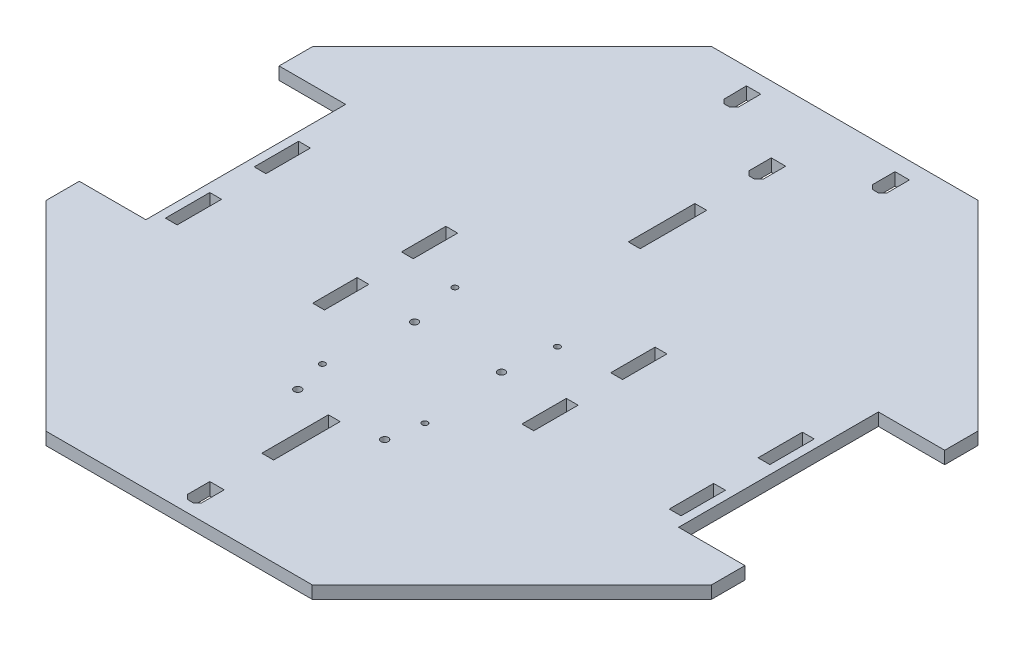
SolidWorks part; units mm, degrees
ref_plane "Front Plane" through (0, 0, 0) normal (0, 0, 1) x (1, 0, 0)
ref_plane "Top Plane" through (0, 0, 0) normal (0, 1, 0) x (1, 0, 0)
ref_plane "Right Plane" through (0, 0, 0) normal (1, 0, 0) x (0, 0, -1)
sketch "Sketch1" plane through (0, 0, 0) normal (0, 1, 0) x (1, 0, 0)
  line L1 (0, 0) -> (254, 0)
  line L2 (0, 0) -> (0, 254)
  line L3 (0, 254) -> (254, 254)
  line L4 (254, 0) -> (254, 254)
  dimension "D1" = 254
  dimension "D2" = 254
extrude "Boss-Extrude1" add sketch "Sketch1" along normal blind 4.8
sketch "Sketch2" plane through (0, 4.8, 0) normal (0, 1, 0) x (1, 0, 0)
  line L0 (0, 254) -> (76.2, 254) construction
  line L1 (254, 254) -> (0, 254) construction
  line L2 (0, 254) -> (0, 177.8) construction
  line L3 (0, 254) -> (0, 0) construction
sketch "Sketch4" plane through (0, 4.8, 0) normal (0, 1, 0) x (1, 0, 0)
  line L0 (76.2, 254) -> (0, 177.8)
  line L1 (0, 177.8) -> (0, 254)
  line L2 (0, 254) -> (76.2, 254)
extrude "Cut-Extrude2" cut sketch "Sketch4" against normal through all
sketch "Sketch5" plane through (0, 4.8, 0) normal (0, 1, 0) x (1, 0, 0)
  line L0 (177.8, 254) -> (254, 254) construction
  line L1 (254, 254) -> (76.2, 254) construction
  line L2 (254, 254) -> (254, 177.8) construction
  line L3 (254, 0) -> (254, 254) construction
  line L4 (177.8, 254) -> (254, 177.8)
  line L5 (254, 177.8) -> (254, 254)
  line L6 (254, 254) -> (177.8, 254)
extrude "Cut-Extrude3" cut sketch "Sketch5" against normal blind 4.826
sketch "Sketch9" plane through (0, 4.8, 0) normal (0, 1, 0) x (1, 0, 0)
  line L0 (0, 76.2) -> (0, 0)
  line L1 (0, 177.8) -> (0, 0) construction
  line L2 (0, 0) -> (76.2, 0)
  line L3 (0, 0) -> (254, 0) construction
  line L4 (76.2, 0) -> (0, 76.2)
  dimension "D1" = 76.2
  dimension "D2" = 76.2
extrude "Cut-Extrude5" cut sketch "Sketch9" against normal blind 4.826
sketch "Sketch11" plane through (0, 4.8, 0) normal (0, 1, 0) x (1, 0, 0)
  line L0 (254, 76.2) -> (254, 0)
  line L1 (254, 0) -> (254, 177.8) construction
  line L2 (254, 0) -> (177.8, 0)
  line L3 (76.2, 0) -> (254, 0) construction
  line L4 (177.8, 0) -> (254, 76.2)
  dimension "D1" = 76.2
  dimension "D2" = 76.2
extrude "Cut-Extrude6" cut sketch "Sketch11" against normal blind 4.826
sketch "Sketch16" plane through (0, 0, 0) normal (0, -1, 0) x (1, 0, 0)
  line L3 (155.3, -247.65) -> (155.3, -237.45) construction
  line L8 (254, -76.2) -> (177.8, 0)
  line L9 (177.8, 0) -> (76.2, 0)
  line L10 (76.2, 0) -> (0, -76.2)
  line L11 (0, -76.2) -> (0, -177.8)
  line L12 (0, -177.8) -> (76.2, -254)
  line L13 (76.2, -254) -> (177.8, -254)
  line L14 (177.8, -254) -> (254, -177.8)
  line L15 (254, -177.8) -> (254, -76.2)
  line L16 (254, -76.2) -> (177.8, 0)
  line L17 (177.8, 0) -> (76.2, 0)
  line L18 (76.2, 0) -> (0, -76.2)
  line L19 (0, -76.2) -> (0, -177.8)
  line L20 (0, -177.8) -> (76.2, -254)
  line L21 (76.2, -254) -> (177.8, -254)
  line L22 (177.8, -254) -> (254, -177.8)
  line L23 (254, -177.8) -> (254, -76.2)
  line L43 (154.05, -237.45) -> (152.4, -239.0996)
  line L45 (154.05, -237.45) -> (156.25, -237.45)
  line L46 (157.9, -239.0996) -> (156.25, -237.45)
  line L47 (157.9, -239.0996) -> (157.9, -240.05)
  line L48 (157.9, -240.05) -> (157.9, -241.75)
  line L49 (157.9, -241.75) -> (157.9, -242.075)
  line L50 (157.9, -243.025) -> (157.9, -243.35)
  line L51 (157.9, -242.075) -> (157.9, -243.025)
  line L52 (157.9, -243.35) -> (157.9, -246.2837)
  line L53 (157.9, -246.2837) -> (157.9, -247.2337)
  line L54 (157.9, -247.2337) -> (157.9, -247.65)
  line L55 (157.9, -247.65) -> (152.4, -247.65)
  line L57 (152.4, -247.65) -> (152.4, -239.0996)
  point P24 (155.3, -237.45)
  point P28 (155.3, -247.65)
  dimension "D4" = 2.2
  dimension "D3" = 101.6
  dimension "D5" = 6.35
extrude "Cut-Extrude8" cut sketch "Sketch16" against normal through all flip side to cut
sketch "Sketch17" plane through (0, 0, 0) normal (0, -1, 0) x (1, 0, 0)
  line L8 (254, -76.2) -> (177.8, 0)
  line L9 (177.8, 0) -> (76.2, 0)
  line L10 (76.2, 0) -> (0, -76.2)
  line L11 (0, -76.2) -> (0, -177.8)
  line L12 (0, -177.8) -> (76.2, -254)
  line L13 (76.2, -254) -> (177.8, -254)
  line L14 (177.8, -254) -> (254, -177.8)
  line L15 (254, -177.8) -> (254, -76.2)
  line L16 (254, -76.2) -> (177.8, 0)
  line L17 (177.8, 0) -> (76.2, 0)
  line L18 (76.2, 0) -> (0, -76.2)
  line L19 (0, -76.2) -> (0, -177.8)
  line L20 (0, -177.8) -> (76.2, -254)
  line L21 (76.2, -254) -> (177.8, -254)
  line L22 (177.8, -254) -> (254, -177.8)
  line L23 (254, -177.8) -> (254, -76.2)
  line L38 (125.9, -218.4) -> (128.1, -218.4)
  line L39 (129.75, -220.0496) -> (128.1, -218.4)
  line L40 (129.75, -220.0496) -> (129.75, -221)
  line L41 (129.75, -221) -> (129.75, -222.7)
  line L42 (129.75, -222.7) -> (129.75, -223.025)
  line L43 (129.75, -223.025) -> (129.75, -223.975)
  line L44 (129.75, -223.975) -> (129.75, -224.3)
  line L45 (125.9, -218.4) -> (124.25, -220.0496)
  line L46 (124.25, -221) -> (124.25, -220.0496)
  line L47 (124.25, -222.7) -> (124.25, -221)
  line L48 (124.25, -223.025) -> (124.25, -222.7)
  line L49 (124.25, -223.025) -> (124.25, -223.975)
  line L50 (124.25, -224.3) -> (124.25, -223.975)
  line L51 (124.25, -228.6) -> (124.25, -228.1837)
  line L52 (124.25, -228.15) -> (124.25, -227.2337)
  line L53 (124.25, -227.2337) -> (124.25, -224.3)
  line L54 (129.75, -224.3) -> (129.75, -227.2337)
  line L55 (129.75, -227.2337) -> (129.75, -228.1837)
  line L56 (129.75, -228.1837) -> (129.75, -228.6)
  line L57 (129.75, -228.6) -> (124.25, -228.6)
  line L58 (124.25, -228.1837) -> (124.25, -228.15)
  line L59 (127, -228.6) -> (127, -218.4) construction
  dimension "D3" = 127
  dimension "D4" = 2.2
extrude "Cut-Extrude17" cut sketch "Sketch17" against normal through all flip side to cut
extrude "Cut-Extrude18" cut sketch "Sketch18" against normal through all flip side to cut
sketch "Sketch18" plane through (166.6617, 4.8, -135.9887) normal (0, 1, 0) x (1, 0, 0)
  line L1 (-65.4617, 103.1109) -> (-65.4617, 111.6613)
  line L16 (-90.5617, -135.9887) -> (11.0383, -135.9887)
  line L17 (11.0383, -135.9887) -> (87.2383, -59.7887)
  line L18 (87.2383, -59.7887) -> (87.2383, 41.8113)
  line L19 (87.2383, 41.8113) -> (11.0383, 118.0113)
  line L20 (11.0383, 118.0113) -> (-90.5617, 118.0113)
  line L21 (-90.5617, 118.0113) -> (-166.7617, 41.8113)
  line L22 (-166.7617, 41.8113) -> (-166.7617, -59.7887)
  line L23 (-166.7617, -59.7887) -> (-90.5617, -135.9887)
  line L43 (-69.2117, 101.4613) -> (-70.8124, 103.0617)
  line L44 (-69.2117, 101.4613) -> (-67.0117, 101.4613)
  line L45 (-65.4617, 103.1109) -> (-67.0117, 101.4613)
  line L51 (-65.4617, 111.6613) -> (-70.9617, 111.6613)
  line L54 (-70.8124, 103.0617) -> (-70.9617, 111.6613)
  dimension "D3" = 6.35
extrude "Cut-Extrude19" cut sketch "Sketch19" against normal through all flip side to cut
sketch "Sketch19" plane through (277.6323, 0, -234.2881) normal (0, -1, 0) x (1, 0, 0)
  line L0 (-23.6323, 158.0881) -> (-23.6323, 56.4881) construction
  line L2 (-99.9323, -19.7119) -> (-201.4323, -19.7119) construction
  line L16 (-23.6323, 158.0881) -> (-99.8323, 234.2881)
  line L17 (-99.8323, 234.2881) -> (-201.4323, 234.2881)
  line L18 (-201.4323, 234.2881) -> (-277.6323, 158.0881)
  line L19 (-277.6323, 158.0881) -> (-277.6323, 56.4881)
  line L20 (-277.6323, 56.4881) -> (-201.4323, -19.7119)
  line L21 (-201.4323, -19.7119) -> (-99.8323, -19.7119)
  line L22 (-99.8323, -19.7119) -> (-23.6323, 56.4881)
  line L23 (-23.6323, 56.4881) -> (-23.6323, 158.0881)
  line L33 (-56.8343, 124.2214) -> (-52.3343, 124.2214)
  line L34 (-56.8343, 124.2214) -> (-56.8343, 141.1547)
  line L35 (-56.8343, 141.1547) -> (-52.3343, 141.1547)
  line L36 (-52.3343, 124.2214) -> (-52.3343, 141.1547)
  line L37 (-56.8343, 124.2214) -> (-52.3343, 141.1547) construction
  line L38 (-56.8343, 141.1547) -> (-52.3343, 124.2214) construction
  line L41 (-56.8343, 90.3547) -> (-52.3343, 90.3547)
  line L42 (-56.8343, 90.3547) -> (-56.8343, 107.2881)
  line L43 (-56.8343, 107.2881) -> (-52.3343, 107.2881)
  line L44 (-52.3343, 90.3547) -> (-52.3343, 107.2881)
  line L45 (-56.8343, 90.3547) -> (-52.3343, 107.2881) construction
  line L46 (-56.8343, 107.2881) -> (-52.3343, 90.3547) construction
  dimension "D1" = 28.702
  dimension "D2" = 28.702
  dimension "D4" = 16.9333
  dimension "D3" = 143.9333
  dimension "D5" = 4.5
  dimension "D6" = 16.9333
  dimension "D7" = 4.5
  dimension "D8" = 16.9333
ref_plane "Plane2" through (126.95, 0, 0) normal (1, 0, 0) x (0, 0, -1)
mirror "Mirror2" about plane through (126.95, 0, 0) normal (1, 0, 0) of "Cut-Extrude19"
extrude "Cut-Extrude22" cut sketch "Sketch32" against normal blind 25.4
sketch "Sketch32" plane through (254, 6.7388, -234.2881) normal (1, 0, 0) x (0, 1, 0)
  line L1 (-6.7388, 145.3881) -> (-1.9388, 145.3881)
  line L2 (-6.7388, 145.3881) -> (-6.7388, 69.1881)
  line L3 (-6.7388, 69.1881) -> (-1.9388, 69.1881)
  line L4 (-1.9388, 145.3881) -> (-1.9388, 69.1881)
  line L5 (-6.7388, 145.3881) -> (-1.9388, 69.1881) construction
  line L6 (-6.7388, 69.1881) -> (-1.9388, 145.3881) construction
  point P4 (-4.3388, 107.2881)
extrude "Cut-Extrude23" cut sketch "Sketch33" against normal through all contours L53 L44 L45 L46 L47 L48 L49 L50 L51 L38 L39 L52 L41 L42 L43
sketch "Sketch33" plane through (166.6617, 0, -135.9887) normal (0, -1, 0) x (1, 0, 0)
  line L0 (-39.8327, 121.3869) -> (-39.8327, 131.5869)
  line L24 (62.1673, 47.0887) -> (87.1673, 47.0887)
  line L25 (87.1673, 47.0887) -> (87.1673, 59.7887)
  line L26 (87.1673, 59.7887) -> (10.9673, 135.9887)
  line L27 (10.9673, 135.9887) -> (-90.6327, 135.9887)
  line L28 (-90.6327, 135.9887) -> (-166.8327, 59.7887)
  line L29 (-166.8327, 59.7887) -> (-166.8327, 47.0887)
  line L30 (-166.8327, -41.8113) -> (-90.6327, -118.0113)
  line L31 (-90.6327, -118.0113) -> (10.9673, -118.0113)
  line L32 (10.9673, -118.0113) -> (87.1673, -41.8113)
  line L33 (87.1673, -41.8113) -> (87.1673, -29.1113)
  line L34 (87.1673, -29.1113) -> (62.1673, -29.1113)
  line L35 (62.1673, -29.1113) -> (62.1673, 47.0887)
  line L38 (-42.5827, 122.7532) -> (-42.5827, 125.6869)
  line L39 (-42.5827, 121.8369) -> (-42.5827, 122.7532)
  line L41 (-37.0827, 121.3869) -> (-42.5827, 121.3869)
  line L42 (-37.0827, 121.8032) -> (-37.0827, 121.3869)
  line L43 (-37.0827, 122.7532) -> (-37.0827, 121.8032)
  line L44 (-37.0827, 129.9373) -> (-38.7327, 131.5869)
  line L45 (-40.9327, 131.5869) -> (-38.7327, 131.5869)
  line L46 (-40.9327, 131.5869) -> (-42.5827, 129.9373)
  line L47 (-42.5827, 128.9869) -> (-42.5827, 129.9373)
  line L48 (-42.5827, 127.2869) -> (-42.5827, 128.9869)
  line L49 (-42.5827, 126.9619) -> (-42.5827, 127.2869)
  line L50 (-42.5827, 126.9619) -> (-42.5827, 126.0119)
  line L51 (-42.5827, 125.6869) -> (-42.5827, 126.0119)
  line L52 (-42.5827, 121.8369) -> (-42.5827, 121.3869)
  line L53 (-37.0827, 122.7532) -> (-37.0827, 129.9373)
  line L71 (-141.8327, -29.1113) -> (-166.8327, -29.1113)
  line L73 (-166.8327, -29.1113) -> (-166.8327, -41.8113)
  line L75 (-166.8327, 47.0887) -> (-141.8327, 47.0887)
  line L77 (-141.8327, 47.0887) -> (-141.8327, -29.1113)
  point P7 (-39.8327, 131.5869)
  point P15 (-39.8327, 121.3869)
  dimension "D3" = 127
extrude "Cut-Extrude24" cut sketch "Sketch34" against normal blind 25.4
sketch "Sketch34" plane through (0, 6.7388, -234.2881) normal (-1, 0, 0) x (0, -1, 0)
  line L3 (6.7388, 69.1881) -> (1.9388, 69.1881)
  line L8 (6.7388, 69.1881) -> (6.7388, 145.3881)
  line L9 (6.7388, 145.3881) -> (1.9388, 145.3881)
  line L10 (1.9388, 69.1881) -> (1.9388, 145.3881)
  line L11 (6.7388, 69.1881) -> (1.9388, 145.3881) construction
  line L12 (6.7388, 145.3881) -> (1.9388, 69.1881) construction
  point P17 (4.3388, 107.2881)
extrude "Cut-Extrude26" cut sketch "Sketch36" against normal through all
sketch "Sketch36" plane through (277.6323, 0, -234.2881) normal (0, -1, 0) x (1, 0, 0)
  line L0 (-49.0323, 69.1881) -> (-49.0323, 145.3881) construction
  line L1 (-108.5209, 124.2214) -> (-113.0209, 124.2214)
  line L2 (-108.5209, 124.2214) -> (-108.5209, 141.1547)
  line L3 (-108.5209, 141.1547) -> (-113.0209, 141.1547)
  line L4 (-113.0209, 124.2214) -> (-113.0209, 141.1547)
  line L5 (-108.5209, 124.2214) -> (-113.0209, 141.1547) construction
  line L6 (-108.5209, 141.1547) -> (-113.0209, 124.2214) construction
  line L10 (-113.0209, 90.3547) -> (-108.5209, 90.3547)
  line L11 (-113.0209, 90.3547) -> (-113.0209, 107.2881)
  line L12 (-113.0209, 107.2881) -> (-108.5209, 107.2881)
  line L13 (-108.5209, 90.3547) -> (-108.5209, 107.2881)
  line L14 (-113.0209, 90.3547) -> (-108.5209, 107.2881) construction
  line L15 (-113.0209, 107.2881) -> (-108.5209, 90.3547) construction
  point P4 (-110.3603, 132.9109)
  point P5 (-110.7709, 141.1547)
  point P13 (-110.6536, 98.8214)
  dimension "D7" = 4.5
  dimension "D1" = 16.9333
  dimension "D2" = 16.9333
  dimension "D3" = 4.5
  dimension "D4" = 4.5
  dimension "D5" = 59.4886
  dimension "D6" = 59.4886
mirror "Mirror3" about plane through (126.95, 0, 0) normal (1, 0, 0) of "Cut-Extrude26"
sketch "Sketch37" plane through (0, 4.8, 0) normal (0, 1, 0) x (1, 0, 0)
  line L1 (129.25, 173.5667) -> (124.75, 173.5667)
  line L2 (129.25, 173.5667) -> (129.25, 198.9667)
  line L3 (129.25, 198.9667) -> (124.75, 198.9667)
  line L4 (124.75, 173.5667) -> (124.75, 198.9667)
  line L5 (129.25, 173.5667) -> (124.75, 198.9667) construction
  line L6 (129.25, 198.9667) -> (124.75, 173.5667) construction
  line L7 (177.7, 254) -> (76.2, 254) construction
  line L8 (0, 177.8) -> (0, 165.1) construction
  point P4 (127, 186.2667)
  point P5 (127, 198.9667)
  dimension "D1" = 25.4
  dimension "D2" = 4.5
  dimension "D4" = 55.0333
  dimension "D3" = 127
extrude "Cut-Extrude27" cut sketch "Sketch37" against normal through all
sketch "Sketch46" plane through (0, 0, 0) normal (0, -1, 0) x (1, 0, 0)
  line L16 (25.4, -165.1) -> (0, -165.1)
  line L17 (0, -165.1) -> (0, -177.8)
  line L18 (0, -177.8) -> (76.2, -254)
  line L19 (76.2, -254) -> (177.7, -254)
  line L20 (177.7, -254) -> (253.9, -177.8)
  line L21 (177.7, -254) -> (253.9, -177.8)
  line L22 (253.9, -165.1) -> (228.6, -165.1)
  line L23 (228.6, -165.1) -> (228.6, -88.9)
  line L24 (228.6, -88.9) -> (253.9, -88.9)
  line L25 (253.9, -177.8) -> (253.9, -165.1)
  line L26 (253.9, -177.8) -> (253.9, -165.1)
  line L27 (177.7, 0) -> (76.2, 0)
  line L28 (76.2, 0) -> (0, -76.2)
  line L29 (0, -76.2) -> (0, -88.9)
  line L30 (0, -88.9) -> (25.4, -88.9)
  line L31 (25.4, -88.9) -> (25.4, -165.1)
  line L32 (25.4, -165.1) -> (0, -165.1)
  line L33 (0, -165.1) -> (0, -177.8)
  line L34 (0, -177.8) -> (76.2, -254)
  line L35 (76.2, -254) -> (177.7, -254)
  line L38 (253.9, -165.1) -> (228.6, -165.1)
  line L39 (228.6, -165.1) -> (228.6, -88.9)
  line L40 (228.6, -88.9) -> (253.9, -88.9)
  line L43 (177.7, 0) -> (76.2, 0)
  line L44 (76.2, 0) -> (0, -76.2)
  line L45 (0, -76.2) -> (0, -88.9)
  line L46 (0, -88.9) -> (25.4, -88.9)
  line L47 (25.4, -88.9) -> (25.4, -165.1)
  line L48 (253.9, -88.9) -> (253.9, -76.2)
  line L49 (253.9, -88.9) -> (253.9, -76.2)
  line L50 (253.9, -76.2) -> (177.7, 0)
  line L51 (253.9, -76.2) -> (177.7, 0)
  dimension "D1" = 0
sketch "Sketch48" plane through (0, 0, 0) normal (0, -1, 0) x (-1, 0, 0)
  line L0 (-177.7, 0) -> (-76.2, 0) construction
  line L1 (-124.65, 33.8667) -> (-129.15, 33.8667)
  line L2 (-124.65, 33.8667) -> (-124.65, 59.2667)
  line L3 (-124.65, 59.2667) -> (-129.15, 59.2667)
  line L4 (-129.15, 33.8667) -> (-129.15, 59.2667)
  line L5 (-124.65, 33.8667) -> (-129.15, 59.2667) construction
  line L6 (-124.65, 59.2667) -> (-129.15, 33.8667) construction
  line L7 (-253.9, 88.9) -> (-253.9, 76.2) construction
  point P4 (-126.9, 46.5667)
  point P9 (-126.9, 33.8667)
  dimension "D3" = 4.5
  dimension "D1" = 33.8667
  dimension "D2" = 25.4
  dimension "D4" = 127
extrude "Cut-Extrude34" cut sketch "Sketch48" against normal through all
sketch "Sketch49" plane through (0, 0, 0) normal (0, -1, 0) x (1, 0, 0)
  line L16 (25.4, -165.1) -> (0, -165.1)
  line L17 (0, -165.1) -> (0, -177.8)
  line L18 (0, -177.8) -> (76.2, -254)
  line L19 (76.2, -254) -> (177.7, -254)
  line L20 (177.7, -254) -> (253.9, -177.8)
  line L21 (177.7, -254) -> (253.9, -177.8)
  line L22 (253.9, -165.1) -> (228.6, -165.1)
  line L23 (228.6, -165.1) -> (228.6, -88.9)
  line L24 (228.6, -88.9) -> (253.9, -88.9)
  line L25 (253.9, -177.8) -> (253.9, -165.1)
  line L26 (253.9, -177.8) -> (253.9, -165.1)
  line L27 (177.7, 0) -> (76.2, 0)
  line L28 (76.2, 0) -> (0, -76.2)
  line L29 (0, -76.2) -> (0, -88.9)
  line L30 (0, -88.9) -> (25.4, -88.9)
  line L31 (25.4, -88.9) -> (25.4, -165.1)
  line L32 (25.4, -165.1) -> (0, -165.1)
  line L33 (0, -165.1) -> (0, -177.8)
  line L34 (0, -177.8) -> (76.2, -254)
  line L35 (76.2, -254) -> (177.7, -254)
  line L38 (253.9, -165.1) -> (228.6, -165.1)
  line L39 (228.6, -165.1) -> (228.6, -88.9)
  line L40 (228.6, -88.9) -> (253.9, -88.9)
  line L43 (177.7, 0) -> (76.2, 0)
  line L44 (76.2, 0) -> (0, -76.2)
  line L45 (0, -76.2) -> (0, -88.9)
  line L46 (0, -88.9) -> (25.4, -88.9)
  line L47 (25.4, -88.9) -> (25.4, -165.1)
  line L48 (253.9, -88.9) -> (253.9, -76.2)
  line L49 (253.9, -88.9) -> (253.9, -76.2)
  line L50 (253.9, -76.2) -> (177.7, 0)
  line L51 (253.9, -76.2) -> (177.7, 0)
  dimension "D1" = 0
extrude "Cut-Extrude35" cut sketch "Sketch50" against normal through all contours A7 | A6 | A5 | A4
sketch "Sketch50" plane through (0, 4.8, -436.7833) normal (0, 1, 0) x (1, 0, 0)
  line L0 (143.575, -330.4266) -> (143.575, -374.9766) construction
  line L1 (110.425, -330.4266) -> (110.425, -374.9766) construction
  line L2 (25.4, -309.1927) -> (110.425, -309.1927) construction
  line L3 (143.575, -309.1927) -> (228.6, -309.1927) construction
  line L4 (110.425, -374.9766) -> (143.575, -374.9766) construction
  line L5 (143.575, -374.9766) -> (110.425, -330.4266) construction
  line L6 (110.425, -330.4266) -> (143.575, -330.4266) construction
  line L7 (143.575, -330.4266) -> (110.425, -374.9766) construction
  line L8 (228.6, -271.6833) -> (228.6, -347.8833) construction
  line L9 (25.4, -347.8833) -> (25.4, -271.6833) construction
  line L10 (127, -377.5166) -> (127, -374.9766) construction
  line L11 (124.65, -377.5166) -> (129.15, -377.5166) construction
  circle A4 centre (110.425, -374.9766) radius 1.4
  circle A5 centre (143.575, -374.9766) radius 1.4
  circle A6 centre (110.425, -330.4266) radius 1.4
  circle A7 centre (143.575, -330.4266) radius 1.4
  dimension "D1" = 44.55
  dimension "D2" = 33.15
extrude "Cut-Extrude36" cut sketch "Sketch51" against normal through all contours A7 | A6 | A5 | A4
sketch "Sketch51" plane through (0, 4.8, -988.8162) normal (0, 1, 0) x (1, 0, 0)
  line L24 (177.7, -988.8162) -> (253.9, -912.6162)
  line L29 (253.9, -912.6162) -> (253.9, -899.9162)
  line L32 (0, -811.0162) -> (0, -823.7162)
  line L33 (0, -823.7162) -> (25.4, -823.7162)
  line L34 (25.4, -823.7162) -> (25.4, -899.9162)
  line L35 (25.4, -899.9162) -> (0, -899.9162)
  line L36 (0, -899.9162) -> (0, -912.6162)
  line L37 (0, -912.6162) -> (76.2, -988.8162)
  line L38 (76.2, -988.8162) -> (177.7, -988.8162)
  line L41 (253.9, -899.9162) -> (228.6, -899.9162)
  line L42 (228.6, -899.9162) -> (228.6, -823.7162)
  line L43 (228.6, -823.7162) -> (253.9, -823.7162)
  line L46 (177.7, -734.8162) -> (76.2, -734.8162)
  line L47 (76.2, -734.8162) -> (0, -811.0162)
  line L49 (253.9, -823.7162) -> (253.9, -811.0162)
  line L51 (253.9, -811.0162) -> (177.7, -734.8162)
  circle A4 centre (106.7217, -913.9283) radius 1.1
  circle A5 centre (145.8417, -913.9283) radius 1.1
  circle A6 centre (106.7217, -863.3783) radius 1.1
  circle A7 centre (145.8417, -863.3783) radius 1.1
equation "\"MDF\"= 4.8mm"
equation "\"Foamcore\"= 4.6mm"
equation "\"GMaterial\"= \"MDF\""
equation "\"D5@Sketch19\"=\"GMaterial\"-\"LaserCutterOffset\""
equation "\"D7@Sketch19\"=\"GMaterial\"-\"LaserCutterOffset\""
equation "\"BaseWidth\" = 10in"
equation "\"D2@Sketch1\"=\"BaseWidth\""
equation "\"D1@Sketch1\"=\"BaseWidth\""
equation "\"D3@Sketch36\"=\"GMaterial\"-\"LaserCutterOffset\""
equation "\"D4@Sketch36\"=\"GMaterial\"-\"LaserCutterOffset\""
equation "\"PCB\" = 1.6mm"
equation "\"SkidLength\" = 1in"
equation "\"D1@Sketch37\"=\"SkidLength\""
equation "\"D2@Sketch37\"=\"GMaterial\"-\"LaserCutterOffset\""
equation "\"D4@Sketch37\"=1.5 +\"SkidLength\" - 1/3"
equation "\"D3@Sketch48\"=\"GMaterial\"-\"LaserCutterOffset\""
equation "\"SkidClearance\" = 0.4in"
equation "\"MotorMountLength\" = 2in"
equation "\"MotorMountWidth\" = \"GMaterial\""
equation "\"MotorMountHeight\" = 2.25in"
equation "\"UnoStackWidth\" = 77.4mm"
equation "\"UnoStackLength\" = 79.8mm"
equation "\"UnoStackHeight\" = 34.2mm"
equation "\"TallHexRiserHeight\" = 22.2mm"
equation "\"PingPongBallSize\" = 40mm"
equation "\"BarrelLength\" = 9in"
equation "\"BarrelSize\" = \"PingPongBallSize\""
equation "\"PlatformLength\" = 4in"
equation "\"PlatformWidth\" = 6in"
equation "\"WheelWidth\"= 26mm"
equation "\"WheelDiameter\"=2.99213"
equation "\"ServoMountHeight\"=2.49223"
equation "\"ServoGearHeight\" = 0.95330261in"
equation "\"ServoMountLength\"= 1.53774"
equation "\"PivotHoleRadius\"= 0.616358"
equation "\"PlatformMountHeight\" = 3.19"
equation "\"TensionOffSet\"= .3mm"
equation "\"MotorMountWedge\"=0.333333"
equation "\"LaserCutterOffset\"= .3mm"
equation "\"InnerMotorMountOffSet\"=2.34207"
equation "\"D6@Sketch36\"=\"InnerMotorMountOffSet\""
equation "\"D7@Sketch36\"=\"GMaterial\"-\"LaserCutterOffset\""
equation "\"OutterMotorMountOffset\"=1.13"
equation "\"D3@Sketch37\"=\"BaseWidth\"/2"
equation "\"TapeSensorWidth\"=0.228346"
equation "\"D2@Sketch17\"=\"TapeSensorWidth\"-\"LaserCutterOffset\""
equation "\"D3@Sketch17\"=\"BaseWidth\"/2"
equation "\"D2@Sketch16\"=\"TapeSensorWidth\"-\"LaserCutterOffset\""
equation "\"D3@Sketch16\"=\"BaseWidth\"/2 - 1"
equation "\"D1@Sketch18\"=\"TapeSensorWidth\"-\"LaserCutterOffset\""
equation "\"TapeSensorBottomWidth\"=0.098425"
equation "\"D2@Sketch18\"=\"TapeSensorBottomWidth\"-\"LaserCutterOffset\""
equation "\"D4@Sketch16\"=\"TapeSensorBottomWidth\"-\"LaserCutterOffset\""
equation "\"D4@Sketch17\"=\"TapeSensorBottomWidth\"-\"LaserCutterOffset\""
equation "\"TapeSensorTopOffset\"=0.25"
equation "\"D3@Sketch18\"=\"TapeSensorTopOffset\""
equation "\"D5@Sketch16\"=\"TapeSensorTopOffset\""
equation "\"BaseInnerWidth\"=8"
equation "\"D1@Sketch33\"=\"TapeSensorBottomWidth\"-\"LaserCutterOffset\""
equation "\"D2@Sketch33\"=\"TapeSensorWidth\"-\"LaserCutterOffset\""
equation "\"D4@Sketch48\"=\"BaseWidth\"/2"
